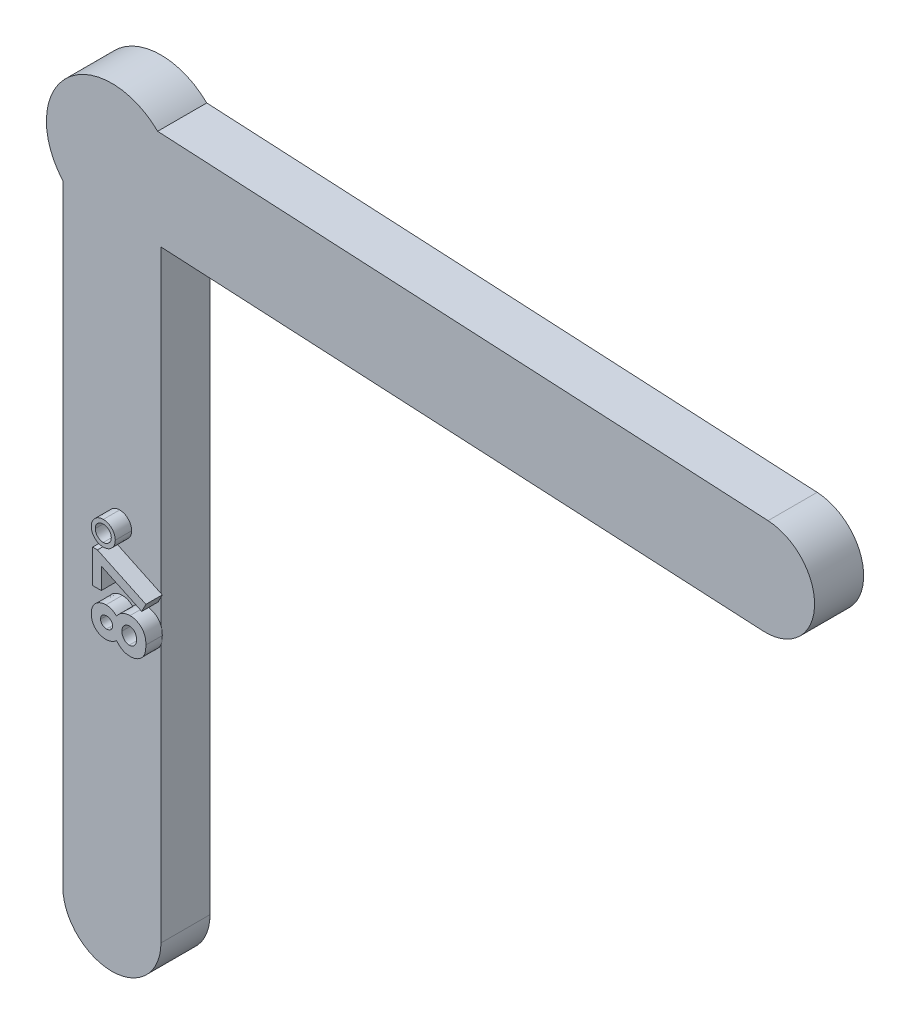
SolidWorks part; units mm, degrees
ref_plane "Front Plane" through (0, 0, 0) normal (0, 0, 1) x (1, 0, 0)
ref_plane "Top Plane" through (0, 0, 0) normal (0, 1, 0) x (1, 0, 0)
ref_plane "Right Plane" through (0, 0, 0) normal (1, 0, 0) x (0, 0, -1)
sketch "Sketch2" plane through (0, 0, 0) normal (0, 0, 1) x (1, 0, 0)
  line L0 (0, 0) -> (0, -40) construction
  line L1 (0, 0) -> (39.9452, -2.0934) construction
  line L2 (40.1022, 0.9025) -> (39.7882, -5.0893) construction
  line L3 (-3, -40) -> (3, -40) construction
  line L4 (-3, -40) -> (-3, -2.6458)
  line L5 (3, -40) -> (3, -3.1613)
  line L6 (40.1022, 0.9025) -> (2.7991, 2.8574)
  line L7 (39.7882, -5.0893) -> (3, -3.1613)
  arc A0 (2.7991, 2.8574) -> (-3, -2.6458) centre (0, 0) ccw
  arc A1 (-3, -40) -> (3, -40) centre (0, -40) ccw
  arc A2 (40.1022, 0.9025) -> (39.7882, -5.0893) centre (39.9452, -2.0934) cw
  point P12 (39.9452, -2.0934)
  dimension "D3" = 3
  dimension "D4" = 8
  dimension "D1" = 40
  dimension "D2" = 87
extrude "Boss-Extrude1" add sketch "Sketch2" along normal blind 3 contours A0 L4 A1 L5 L7 A2 L6
sketch "Sketch3" plane through (0, 0, 3) normal (0, 0, 1) x (1, 0, 0)
  text T0 "<b>87°</b>"
extrude "Boss-Extrude2" add sketch "Sketch3" along normal blind 1
